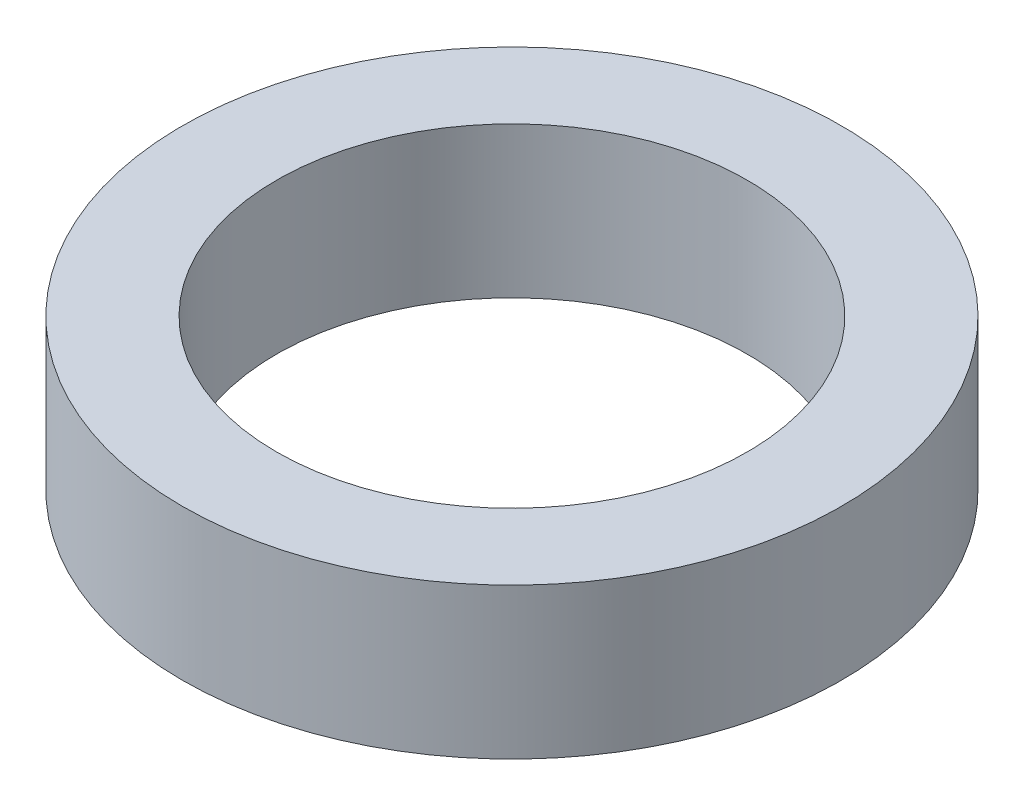
SolidWorks part; units mm, degrees
ref_plane "Front Plane" through (0, 0, 0) normal (0, 0, 1) x (1, 0, 0)
ref_plane "Top Plane" through (0, 0, 0) normal (0, 1, 0) x (1, 0, 0)
ref_plane "Right Plane" through (0, 0, 0) normal (1, 0, 0) x (0, 0, -1)
sketch "Sketch1" plane through (0, 0, 0) normal (0, 1, 0) x (1, 0, 0)
  circle A0 centre (0, 0) radius 3.9688
  circle A1 centre (0, 0) radius 5.5562
  dimension "D1" = 7.9375
  dimension "D2" = 11.1125
extrude "Boss-Extrude1" add sketch "Sketch1" along normal blind 2.54 contours A1 A0
